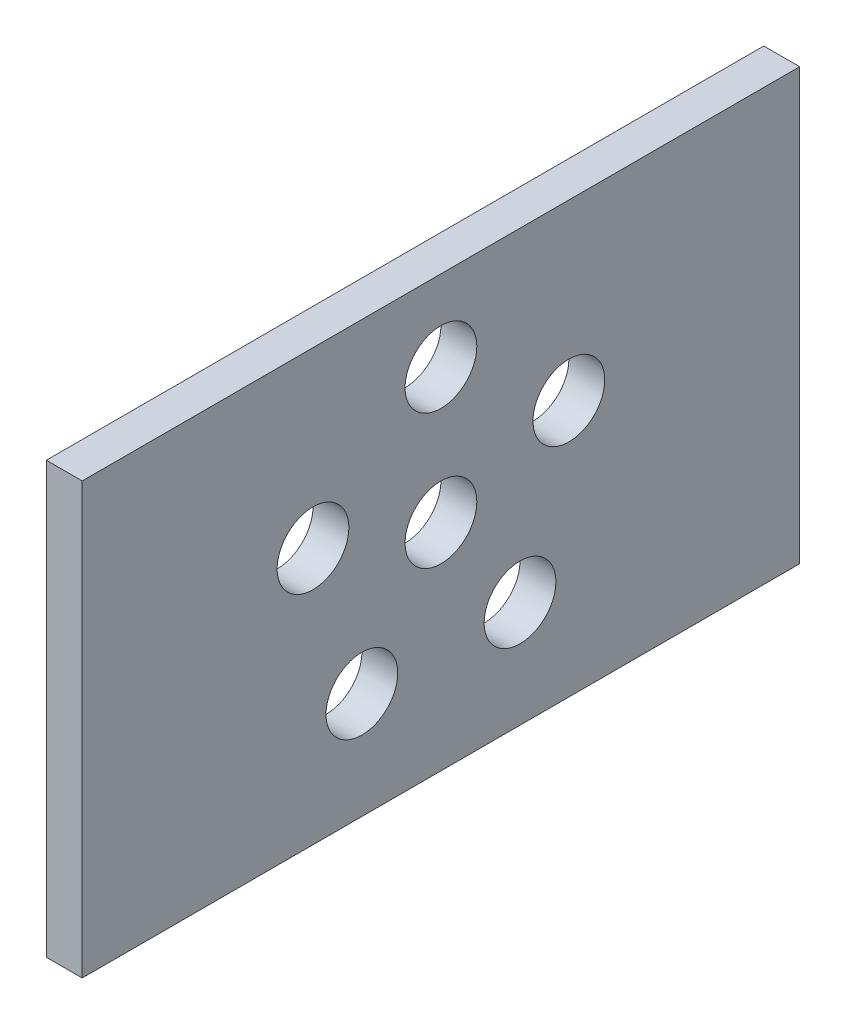
SolidWorks part; units mm, degrees
ref_plane "Front Plane" through (0, 0, 0) normal (0, 0, 1) x (1, 0, 0)
ref_plane "Top Plane" through (0, 0, 0) normal (0, 1, 0) x (1, 0, 0)
ref_plane "Right Plane" through (0, 0, 0) normal (1, 0, 0) x (0, 0, -1)
sketch "Sketch1" plane through (0, 0, 0) normal (1, 0, 0) x (0, 0, -1)
  line L1 (-31.75, -19.05) -> (31.75, -19.05)
  line L2 (-31.75, -19.05) -> (-31.75, 19.05)
  line L3 (-31.75, 19.05) -> (31.75, 19.05)
  line L4 (31.75, -19.05) -> (31.75, 19.05)
  line L5 (-31.75, -19.05) -> (31.75, 19.05) construction
  line L6 (-31.75, 19.05) -> (31.75, -19.05) construction
  circle A1 centre (0, 0) radius 3.175
  dimension "D1" = 63.5
  dimension "ID" = 6.35
  dimension "D2" = 38.1
extrude "Boss-Extrude1" add sketch "Sketch1" along normal blind 3.175
sketch "Sketch2" plane through (0, 0, 0) normal (1, 0, 0) x (0, 0, -1)
  line L0 (-31.75, 0) -> (31.75, 0) construction
  line L3 (31.75, -19.05) -> (31.75, 19.05) construction
  line L4 (-31.75, -19.05) -> (31.75, 19.05) construction
  circle A0 centre (0, 11.9062) radius 3.175
  circle A2 centre (0, 0) radius 11.9062 construction
  point P6 (0, 0)
  point P12 (0, 0)
  dimension "D2" = 6.35
  dimension "D1" = 11.9062
extrude "Cut-Extrude1" cut sketch "Sketch2" along normal through all
pattern_circular "CirPattern1" count 5 over 360 about axis through (0, 0, 0) along (1, 0, 0) of "Cut-Extrude1"
